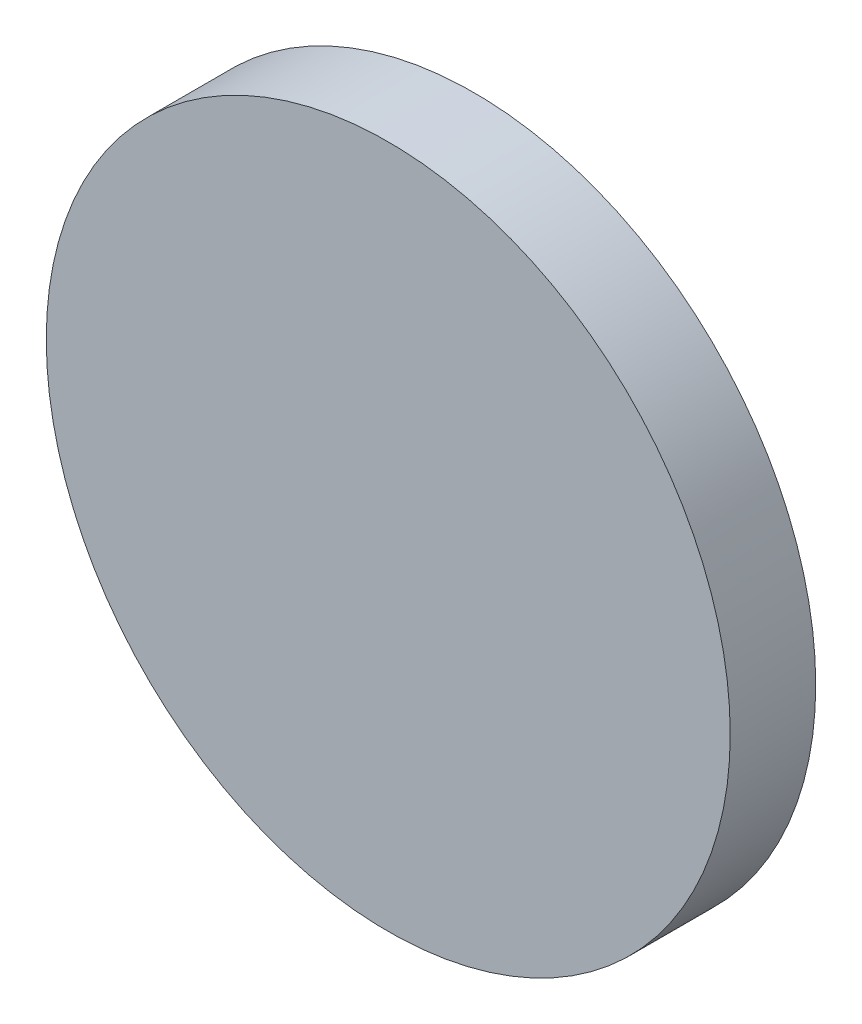
SolidWorks part; units mm, degrees
ref_plane "前视基准面" through (0, 0, 0) normal (0, 0, 1) x (1, 0, 0)
ref_plane "上视基准面" through (0, 0, 0) normal (0, 1, 0) x (1, 0, 0)
ref_plane "右视基准面" through (0, 0, 0) normal (1, 0, 0) x (0, 0, -1)
sketch "草图1" plane through (0, 0, 0) normal (0, 0, 1) x (1, 0, 0)
  circle A0 centre (0, 0) radius 40
extrude "凸台-拉伸1" add sketch "草图1" along normal blind 10
